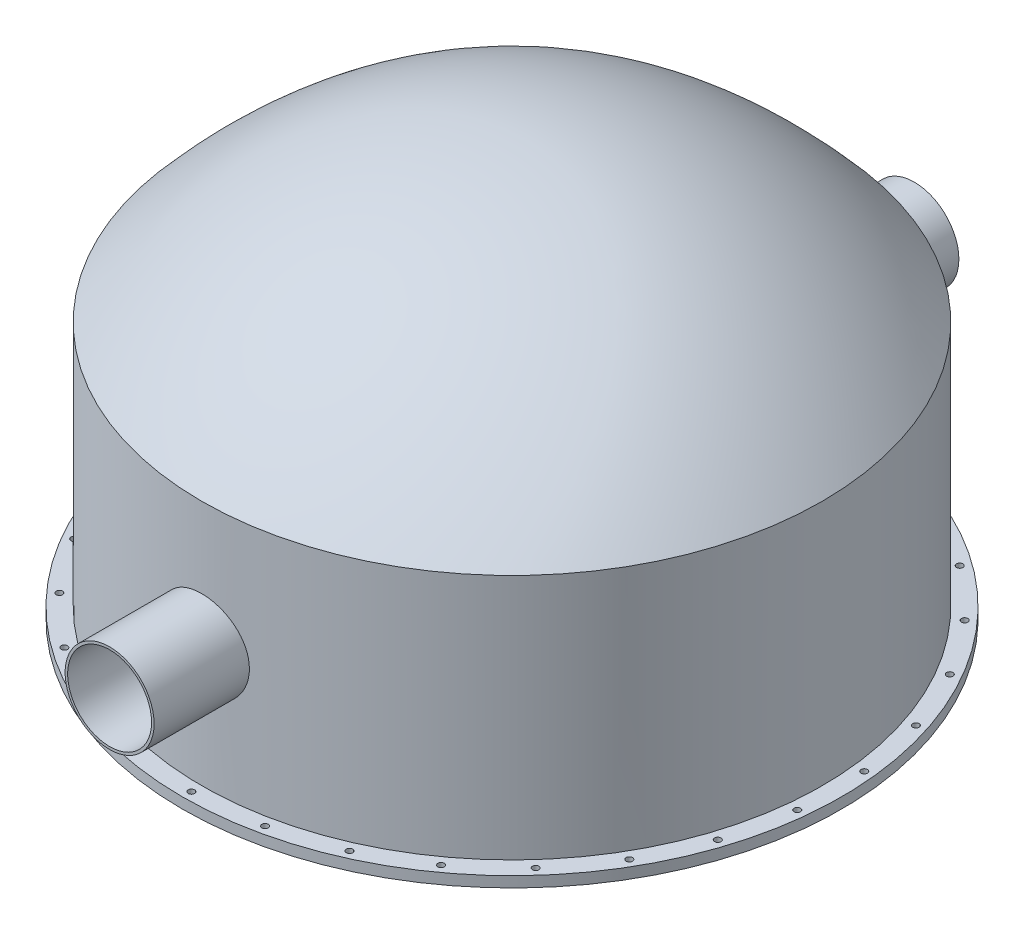
SolidWorks part; units mm, degrees
ref_plane "Front Plane" through (0, 0, 0) normal (0, 0, 1) x (1, 0, 0)
ref_plane "Top Plane" through (0, 0, 0) normal (0, 1, 0) x (1, 0, 0)
ref_plane "Right Plane" through (0, 0, 0) normal (1, 0, 0) x (0, 0, -1)
sketch "Sketch1" plane through (0, 0, 0) normal (1, 0, 0) x (0, 0, -1)
  line L0 (1447.7499, 0) -> (0, 0) construction
  line L1 (0, 0) -> (0, 1626.7153) construction
  line L2 (-2081.13, 0) -> (-2081.13, -1744.12)
  line L3 (-931.3985, 1044.41) -> (931.3985, 1044.41) construction
  line L4 (-2126.02, 16.9087) -> (-2126.02, -1671.12)
  line L5 (-2081.13, -1744.12) -> (-2258.02, -1744.12)
  line L6 (-2258.02, -1744.12) -> (-2258.02, -1671.12)
  line L7 (-2258.02, -1671.12) -> (-2126.02, -1671.12)
  line L8 (0, 1089.3) -> (0, 1044.41)
  line L9 (-2126.02, 16.9087) -> (-2126.02, -1744.12) construction
  spline S0 degree 2 poles (0, 1044.41) (-1164.2481, 1044.41) (-2081.13, 0) knots 0 0 0 1 1 1
  spline S1 degree 1 poles (0, 1089.3) (-2126.02, 16.9087) knots 0 0 1 1 construction
  spline S2 degree 2 poles (0, 1089.3) (-223.4621, 1089.3111) (-581.4225, 1026.2119) (-859.8109, 942.0722) (-1130.0194, 824.365) (-1391.8992, 673.2353) (-1613.6933, 511.8966) (-1768.177, 381.1304) (-1874.4808, 282.365) (-1949.432, 207.9512) (-2001.4413, 154.0583) (-2038.3467, 114.598) (-2064.0667, 86.5254) (-2082.3772, 66.2322) (-2095.1661, 51.9146) (-2104.2861, 41.627) (-2110.6619, 34.3993) (-2115.2157, 29.2163) (-2121.5106, 22.0449) (-2126.02, 16.9087) knots 0 0 0 0.188641 0.314401 0.440161 0.565922 0.691682 0.786003 0.848883 0.896043 0.927483 0.951063 0.966783 0.978573 0.986433 0.992328 0.996258 0.999206 1.001171 1.006083 1.006083 1.006083
  dimension "D1" = 1044.41
  dimension "D2" = 2081.13
  dimension "D3" = 1744.12
  dimension "D5" = 132
  dimension "D6" = 73
  dimension "D4" = 44.89
revolve "Revolve1" add sketch "Sketch1" angle 360 about L1
ref_plane "Plane1" through (0, 0, 2757) normal (0, 0, 1) x (1, 0, 0)
sketch "Sketch3" plane through (0, 0, 2757) normal (0, 0, 1) x (1, 0, 0)
  line L0 (-2258.02, -1744.12) -> (2258.02, -1744.12) construction
  circle A0 centre (0, -835.62) radius 304.8
  dimension "D1" = 609.6
  dimension "D2" = 908.5
extrude "Boss-Extrude1" add sketch "Sketch3" against normal up to surface up to face at (0, -1671.12, -2126.02)
mirror "Mirror1" about plane through (0, 0, 0) normal (0, 0, 1) of "Boss-Extrude1"
sketch "Sketch4" plane through (0, 0, 2757) normal (0, 0, 1) x (1, 0, 0)
  circle A0 centre (0, -835.62) radius 287.4
  dimension "D1" = 574.8
extrude "Cut-Extrude1" cut sketch "Sketch4" against normal through all
sketch "Sketch5" plane through (0, -1744.12, 0) normal (0, -1, 0) x (1, 0, 0)
  circle A0 centre (0, 0) radius 2196.0235 construction
  circle A1 centre (0, 2196.0235) radius 22
  circle A2 centre (456.579, 2148.0351) radius 22
  circle A3 centre (893.2032, 2006.1673) radius 22
  circle A4 centre (1290.7902, 1776.6203) radius 22
  circle A5 centre (1631.9635, 1469.4265) radius 22
  circle A6 centre (1901.8121, 1098.0118) radius 22
  circle A7 centre (2088.5425, 678.6086) radius 22
  circle A8 centre (2183.9935, 229.547) radius 22
  circle A9 centre (2183.9935, -229.547) radius 22
  circle A10 centre (2088.5425, -678.6086) radius 22
  circle A11 centre (1901.8121, -1098.0117) radius 22
  circle A12 centre (1631.9635, -1469.4265) radius 22
  circle A13 centre (1290.7902, -1776.6203) radius 22
  circle A14 centre (893.2032, -2006.1673) radius 22
  circle A15 centre (456.579, -2148.0351) radius 22
  circle A16 centre (0, -2196.0235) radius 22
  circle A17 centre (-456.579, -2148.0351) radius 22
  circle A18 centre (-893.2032, -2006.1673) radius 22
  circle A19 centre (-1290.7902, -1776.6203) radius 22
  circle A20 centre (-1631.9635, -1469.4265) radius 22
  circle A21 centre (-1901.8121, -1098.0118) radius 22
  circle A22 centre (-2088.5425, -678.6086) radius 22
  circle A23 centre (-2183.9935, -229.547) radius 22
  circle A24 centre (-2183.9935, 229.547) radius 22
  circle A25 centre (-2088.5425, 678.6086) radius 22
  circle A26 centre (-1901.8121, 1098.0117) radius 22
  circle A27 centre (-1631.9635, 1469.4265) radius 22
  circle A28 centre (-1290.7902, 1776.6203) radius 22
  circle A29 centre (-893.2032, 2006.1673) radius 22
  circle A30 centre (-456.579, 2148.0351) radius 22
  point P65 (0, 0)
  dimension "D1" = 44
  dimension "D2" = 30
extrude "Cut-Extrude2" cut sketch "Sketch5" against normal up to next (73 mm away)
